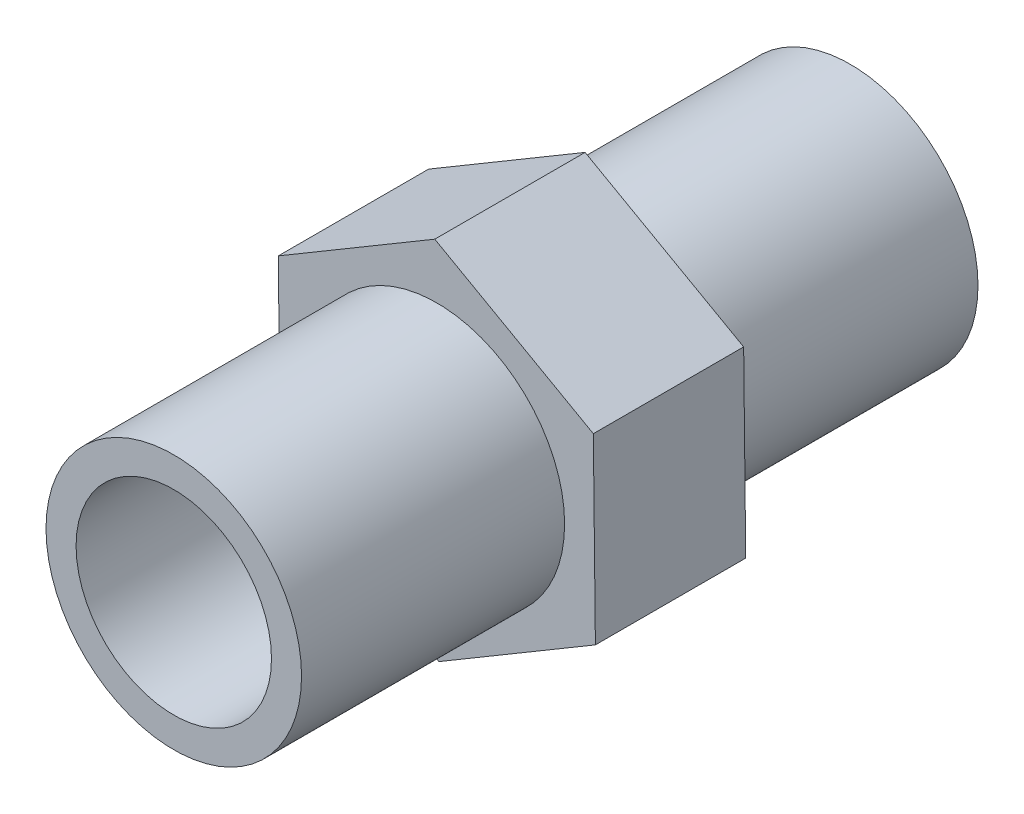
SolidWorks part; units mm, degrees
ref_plane "Front Plane" through (0, 0, 0) normal (0, 0, 1) x (1, 0, 0)
ref_plane "Top Plane" through (0, 0, 0) normal (0, 1, 0) x (1, 0, 0)
ref_plane "Right Plane" through (0, 0, 0) normal (1, 0, 0) x (0, 0, -1)
sketch "Sketch1" plane through (0, 0, 0) normal (0, 0, 1) x (1, 0, 0)
  circle A0 centre (0, 0) radius 8.5
  dimension "D1" = 17
extrude "Extrude-Thin1" add sketch "Sketch1" along normal mid plane 45 thin thin type one direction reverse wall 2
sketch "Sketch2" plane through (0, 0, 0) normal (0, 0, 1) x (1, 0, 0)
  line L1 (10.4111, 6.1685) -> (-0.1365, 12.1005)
  line L2 (-0.1365, 12.1005) -> (-10.5476, 5.932)
  line L3 (-10.5476, 5.932) -> (-10.4111, -6.1685)
  line L4 (-10.4111, -6.1685) -> (0.1365, -12.1005)
  line L5 (0.1365, -12.1005) -> (10.5476, -5.932)
  line L6 (10.5476, -5.932) -> (10.4111, 6.1685)
  circle A0 centre (0, 0) radius 10.48 construction
extrude "Boss-Extrude1" add sketch "Sketch2" along normal mid plane 10
